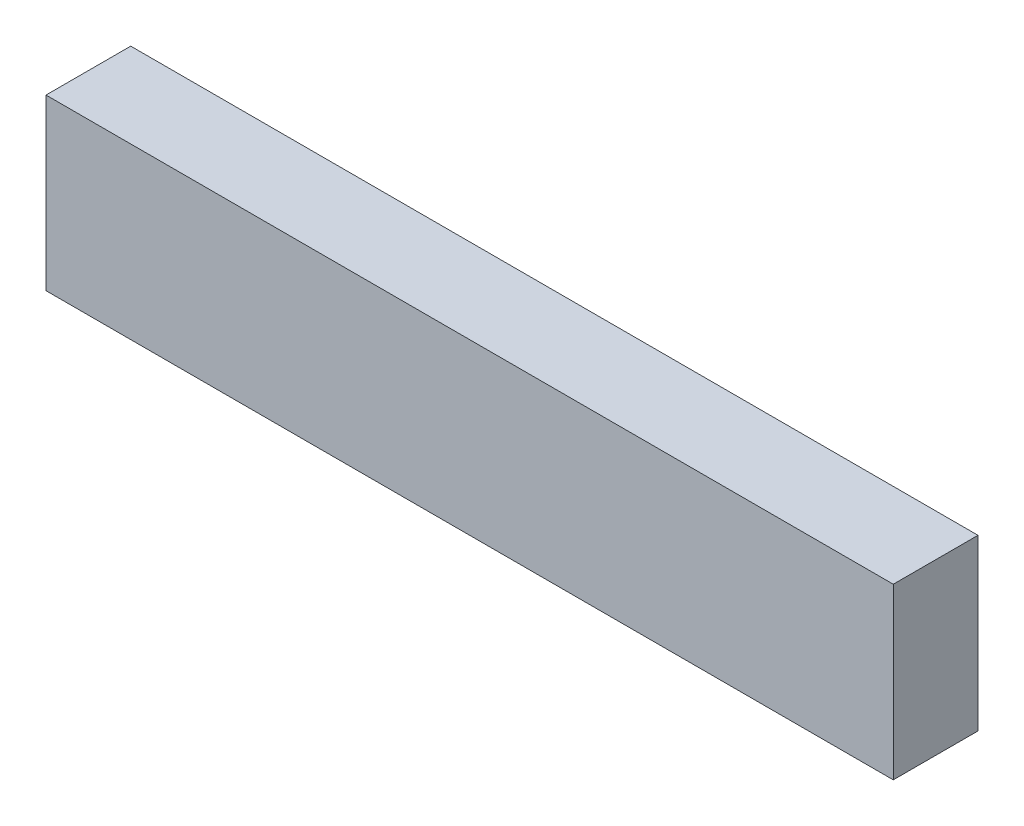
SolidWorks part; units mm, degrees
ref_plane "Front Plane" through (0, 0, 0) normal (0, 0, 1) x (1, 0, 0)
ref_plane "Top Plane" through (0, 0, 0) normal (0, 1, 0) x (1, 0, 0)
ref_plane "Right Plane" through (0, 0, 0) normal (1, 0, 0) x (0, 0, -1)
sketch "Sketch2" plane through (0, 0, 0) normal (0, 1, 0) x (1, 0, 0)
  line L1 (-50, -5) -> (50, -5)
  line L2 (-50, -5) -> (-50, 5)
  line L3 (-50, 5) -> (50, 5)
  line L4 (50, -5) -> (50, 5)
  line L5 (-50, -5) -> (50, 5) construction
  line L6 (-50, 5) -> (50, -5) construction
  point P0 (0, 0)
  dimension "D1" = 100
  dimension "D2" = 10
extrude "Boss-Extrude2" add sketch "Sketch2" along normal mid plane 20
